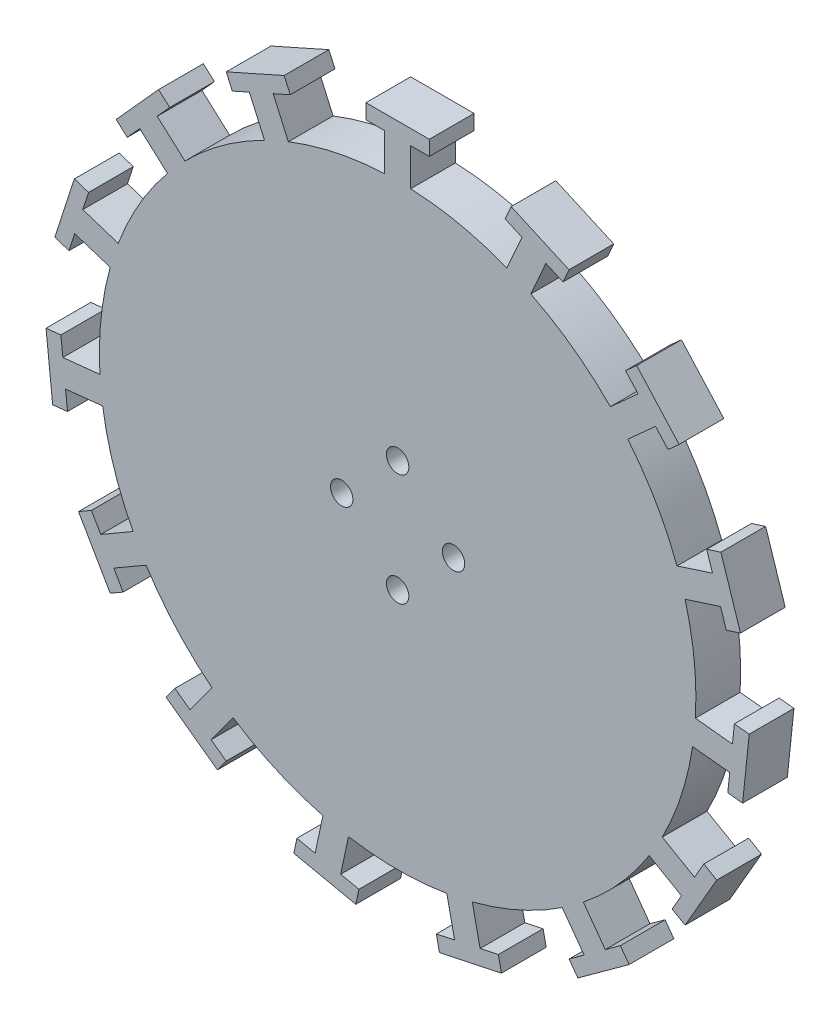
SolidWorks part; units mm, degrees
ref_plane "Front Plane" through (0, 0, 0) normal (0, 0, 1) x (1, 0, 0)
ref_plane "Top Plane" through (0, 0, 0) normal (0, 1, 0) x (1, 0, 0)
ref_plane "Right Plane" through (0, 0, 0) normal (1, 0, 0) x (0, 0, -1)
sketch "Sketch1" plane through (0, 0, 0) normal (0, 0, 1) x (1, 0, 0)
  circle A0 centre (0, 0) radius 40
  dimension "D1" = 80
extrude "Boss-Extrude1" add sketch "Sketch1" along normal blind 2
sketch "Sketch6" plane through (0, 0, 0) normal (0, 0, 1) x (1, 0, 0)
  line L0 (-1.75, 39.9617) -> (-1.75, 44.9617)
  line L1 (0, 37.6165) -> (0, 55.5597) construction
  line L2 (1.75, 39.9617) -> (1.75, 44.9617)
  line L3 (-1.75, 44.9617) -> (-4.25, 44.9617)
  line L4 (-4.25, 44.9617) -> (-4.25, 46.9617)
  line L5 (-4.25, 46.9617) -> (4.25, 46.9617)
  line L6 (4.25, 46.9617) -> (4.25, 44.9617)
  line L7 (4.25, 44.9617) -> (1.75, 44.9617)
  circle A0 centre (0, 0) radius 40 construction
  circle A2 centre (0, 0) radius 40
  arc A3 (-1.75, 39.9617) -> (1.75, 39.9617) centre (0, 0) ccw
  point P11 (0, 0)
  dimension "D1" = 3.5
  dimension "D2" = 5
  dimension "D3" = 2
  dimension "D4" = 2.5
  dimension "D5" = 0
extrude "Boss-Extrude2" add sketch "Sketch6" along normal blind 6
pattern_circular "CirPattern1" count 15 over 360 about axis through (0, 0, 0) along (0, 0, 1) of "Boss-Extrude2"
sketch "Sketch4" plane through (0, 0, 2) normal (0, 0, 1) x (1, 0, 0)
  line L0 (0, -3.3) -> (0, 3.3) construction
  circle A0 centre (0, 7.5) radius 1.5
  circle A4 centre (7.5, 0) radius 1.5
  circle A5 centre (0, -7.5) radius 1.5
  circle A6 centre (-7.5, 0) radius 1.5
  point P4 (0, 2.6948)
  point P5 (0, 6.7691)
  point P6 (0, 0)
  point P15 (0, 0)
  dimension "D1" = 3
  dimension "D2" = 7.5
  dimension "D3" = 4
extrude "Cut-Extrude2" cut sketch "Sketch4" against normal mid plane 20
equation "\"diameter\"=80"
equation "\"D1@Plane2\"=\"diameter\"/2"
